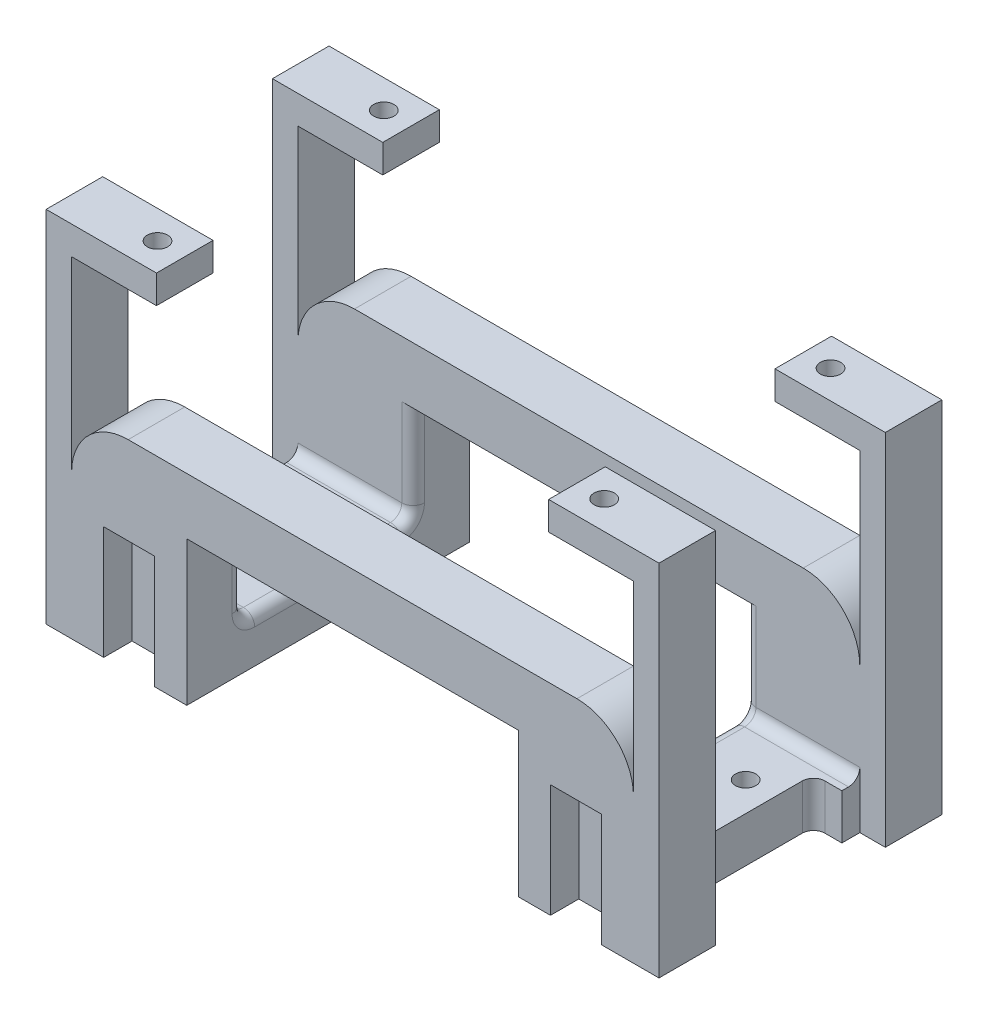
SolidWorks part; units mm, degrees
ref_plane "Front Plane" through (0, 0, 0) normal (0, 0, 1) x (1, 0, 0)
ref_plane "Top Plane" through (0, 0, 0) normal (0, 1, 0) x (1, 0, 0)
ref_plane "Right Plane" through (0, 0, 0) normal (1, 0, 0) x (0, 0, -1)
sketch "Sketch1" plane through (0, 0, 0) normal (0, 0, 1) x (1, 0, 0)
  line L0 (-68.6919, -39.7304) -> (-48.3319, -39.7304)
  line L1 (-48.3319, -39.7304) -> (-48.3319, -14.2304)
  line L2 (-48.3319, -14.2304) -> (10.2681, -14.2304)
  line L3 (10.2681, -14.2304) -> (10.2681, -39.7304)
  line L4 (10.2681, -39.7304) -> (30.6281, -39.7304)
  line L5 (30.6281, -39.7304) -> (30.6281, -4.2304)
  line L6 (30.6281, -4.2304) -> (-68.6919, -4.2304)
  line L7 (-68.6919, -4.2304) -> (-68.6919, -39.7304)
  line L8 (-48.3319, -14.2304) -> (-48.3319, -4.2304) construction
  dimension "D1" = 58.6
  dimension "D2" = 25.5
  dimension "D3" = 99.32
  dimension "D4" = 10
extrude "Boss-Extrude1" add sketch "Sketch1" along normal blind 10
sketch "Sketch2" plane through (0, 0, 10) normal (0, 0, 1) x (1, 0, 0)
  line L0 (-48.3319, -39.7304) -> (-48.3319, -14.2304) construction
  line L1 (-68.6919, -39.7304) -> (-48.3319, -39.7304)
  line L2 (-68.6919, -39.7304) -> (-68.6919, -31.7304)
  line L3 (-68.6919, -31.7304) -> (-48.3319, -31.7304)
  line L4 (-48.3319, -39.7304) -> (-48.3319, -31.7304)
  line L5 (30.6281, -39.7304) -> (30.6281, -4.2304) construction
  line L6 (10.2681, -39.7304) -> (30.6281, -39.7304)
  line L7 (10.2681, -39.7304) -> (10.2681, -31.7304)
  line L8 (10.2681, -31.7304) -> (30.6281, -31.7304)
  line L9 (30.6281, -39.7304) -> (30.6281, -31.7304)
  dimension "D1" = 8
extrude "Boss-Extrude2" add sketch "Sketch2" along normal blind 30
sketch "Sketch3" plane through (0, 0, 40) normal (0, 0, 1) x (1, 0, 0)
  line L0 (-68.6919, -39.7304) -> (-68.6919, -4.2304)
  line L1 (-68.6919, -4.2304) -> (30.6281, -4.2304)
  line L2 (30.6281, -4.2304) -> (30.6281, -39.7304)
  line L3 (30.6281, -39.7304) -> (10.2681, -39.7304)
  line L4 (10.2681, -39.7304) -> (10.2681, -14.2304)
  line L5 (10.2681, -14.2304) -> (-48.3319, -14.2304)
  line L6 (-48.3319, -14.2304) -> (-48.3319, -39.7304)
  line L7 (-48.3319, -39.7304) -> (-68.6919, -39.7304)
  line L8 (-48.3319, -39.7304) -> (-48.3319, -14.2304) construction
  line L10 (30.6281, -39.7304) -> (30.6281, -4.2304) construction
extrude "Boss-Extrude3" add sketch "Sketch3" along normal blind 10
sketch "Sketch4" plane through (0, -31.7304, 0) normal (0, 1, 0) x (1, 0, 0)
  line L0 (-68.6919, -25) -> (30.6281, -25) construction
  line L1 (-68.6919, -40) -> (-68.6919, -10) construction
  line L3 (30.6281, -40) -> (30.6281, -10) construction
  line L4 (-58.5119, -10) -> (-58.5119, -40) construction
  line L5 (-48.3319, -10) -> (-68.6919, -10) construction
  line L6 (-48.3319, -40) -> (-68.6919, -40) construction
  line L7 (20.4481, -10) -> (20.4481, -40) construction
  line L8 (30.6281, -10) -> (10.2681, -10) construction
  line L9 (30.6281, -40) -> (10.2681, -40) construction
  circle A0 centre (-58.5119, -20) radius 1.8
  circle A1 centre (-58.5119, -30) radius 1.8
  circle A2 centre (20.4481, -30) radius 1.8
  circle A3 centre (20.4481, -20) radius 1.8
  dimension "D1" = 3.6
  dimension "D2" = 10
extrude "Cut-Extrude1" cut sketch "Sketch4" against normal through all
sketch "Sketch5" plane through (0, -31.7304, 0) normal (0, 1, 0) x (1, 0, 0)
  line L0 (-68.6919, -40) -> (-68.6919, -10) construction
  line L1 (-68.6919, -13.5) -> (-65.6919, -13.5)
  line L2 (-68.6919, -13.5) -> (-68.6919, -36.5)
  line L3 (-68.6919, -36.5) -> (-65.6919, -36.5)
  line L4 (-63.6919, -15.5) -> (-63.6919, -34.5)
  line L5 (30.6281, -40) -> (30.6281, -10) construction
  line L6 (30.6281, -13.175) -> (27.6281, -13.175)
  line L7 (30.6281, -13.175) -> (30.6281, -36.175)
  line L8 (30.6281, -36.175) -> (27.6281, -36.175)
  line L9 (25.6281, -15.175) -> (25.6281, -34.175)
  line L10 (-68.6919, -25) -> (30.6281, -25) construction
  arc A0 (27.6281, -13.175) -> (25.6281, -15.175) centre (27.6281, -15.175) ccw
  arc A1 (25.6281, -34.175) -> (27.6281, -36.175) centre (27.6281, -34.175) ccw
  arc A2 (-65.6919, -36.5) -> (-63.6919, -34.5) centre (-65.6919, -34.5) ccw
  arc A3 (-63.6919, -15.5) -> (-65.6919, -13.5) centre (-65.6919, -15.5) ccw
  point P20 (-63.6919, -36.5)
  point P23 (-63.6919, -13.5)
  dimension "D3" = 2
  dimension "D1" = 23
  dimension "D2" = 5
extrude "Cut-Extrude2" cut sketch "Sketch5" against normal through all
fillet "Fillet2" radius 10 4 edges at (30.6281, -4.2304, 5) (30.6281, -4.2304, 45) (-68.6919, -4.2304, 5) (-68.6919, -4.2304, 45)
fillet "Fillet3" radius 2 4 edges at (20.4481, -31.7304, 10)
fillet "Fillet4" radius 2 10 edges at (10.2681, -31.1447, 39.4142) (10.2681, -21.9804, 10) (10.2681, -31.1447, 10.5858) (-48.3319, -31.1447, 39.4142) (-48.3319, -31.1447, 10.5858)
sketch "Sketch6" plane through (0, 0, 50) normal (0, 0, 1) x (1, 0, 0)
  line L0 (-68.6919, -39.7304) -> (-48.3319, -39.7304) construction
  line L1 (-63.0119, -39.7304) -> (-54.0119, -39.7304)
  line L2 (-63.0119, -39.7304) -> (-63.0119, -19.7304)
  line L3 (-63.0119, -19.7304) -> (-54.0119, -19.7304)
  line L4 (-54.0119, -39.7304) -> (-54.0119, -19.7304)
  line L5 (10.2681, -39.7304) -> (30.6281, -39.7304) construction
  line L6 (15.9481, -39.7304) -> (24.9481, -39.7304)
  line L7 (15.9481, -39.7304) -> (15.9481, -19.7304)
  line L8 (15.9481, -19.7304) -> (24.9481, -19.7304)
  line L9 (24.9481, -39.7304) -> (24.9481, -19.7304)
  line L10 (-58.5119, -39.7304) -> (-58.5119, 3.4063) construction
  line L11 (20.4481, -39.7304) -> (20.4481, -0.4667) construction
  dimension "D1" = 9
  dimension "D2" = 20
extrude "Cut-Extrude3" cut sketch "Sketch6" against normal blind 5
sketch "Sketch7" plane through (0, 0, 0) normal (0, 0, -1) x (-1, 0, 0)
  line L0 (-20.4481, -39.7304) -> (-20.4481, 23.0749) construction
  line L1 (58.5119, -19.7304) -> (58.5119, -39.7304) construction
  line L2 (-10.2681, -39.7304) -> (-30.6281, -39.7304) construction
  line L3 (68.6919, -39.7304) -> (48.3319, -39.7304) construction
  line L5 (-24.9481, -19.7304) -> (-15.9481, -19.7304)
  line L6 (-24.9481, -19.7304) -> (-24.9481, -39.7304)
  line L7 (-24.9481, -39.7304) -> (-15.9481, -39.7304)
  line L8 (-15.9481, -19.7304) -> (-15.9481, -39.7304)
  line L9 (54.0119, -19.7304) -> (63.0119, -19.7304)
  line L10 (54.0119, -19.7304) -> (54.0119, -39.7304)
  line L11 (54.0119, -39.7304) -> (63.0119, -39.7304)
  line L12 (63.0119, -19.7304) -> (63.0119, -39.7304)
  line L13 (-24.9481, -39.7304) -> (-24.9481, -19.7304) construction
extrude "Cut-Extrude4" cut sketch "Sketch7" against normal blind 5
sketch "Sketch8" plane through (30.6281, 0, 0) normal (1, 0, 0) x (0, 0, -1)
  line L0 (-40, -29.7304) -> (-40, -14.2304) construction
  line L1 (-50, -39.7304) -> (-40, -39.7304)
  line L2 (-50, -39.7304) -> (-50, 23.7696)
  line L3 (-50, 23.7696) -> (-40, 23.7696)
  line L4 (-40, -39.7304) -> (-40, 23.7696)
  line L5 (-10, -39.7304) -> (0, -39.7304)
  line L6 (-10, -39.7304) -> (-10, 23.7696)
  line L7 (-10, 23.7696) -> (0, 23.7696)
  line L8 (0, -39.7304) -> (0, 23.7696)
  line L11 (-10, -29.7304) -> (-10, -14.2304) construction
  line L12 (-40, -14.2304) -> (-50, -14.2304) construction
  dimension "D1" = 38
extrude "Boss-Extrude4" add sketch "Sketch8" along normal blind 4.5
sketch "Sketch9" plane through (30.6281, 0, 0) normal (-1, 0, 0) x (0, 0, 1)
  line L0 (10, 23.7696) -> (10, -14.2304) construction
  line L1 (0, 23.7696) -> (10, 23.7696)
  line L2 (0, 23.7696) -> (0, 18.7696)
  line L3 (0, 18.7696) -> (10, 18.7696)
  line L4 (10, 23.7696) -> (10, 18.7696)
  line L5 (50, 23.7696) -> (50, -14.2304) construction
  line L6 (40, 23.7696) -> (50, 23.7696)
  line L7 (40, 23.7696) -> (40, 18.7696)
  line L8 (40, 18.7696) -> (50, 18.7696)
  line L9 (50, 23.7696) -> (50, 18.7696)
  dimension "D1" = 5
extrude "Boss-Extrude5" add sketch "Sketch9" along normal blind 15
sketch "Sketch10" plane through (-68.6919, 0, 0) normal (-1, 0, 0) x (0, 0, 1)
  line L0 (10, -14.2304) -> (10, -29.7304) construction
  line L1 (0, -39.7304) -> (10, -39.7304)
  line L2 (0, -39.7304) -> (0, 23.7696)
  line L3 (0, 23.7696) -> (10, 23.7696)
  line L4 (10, -39.7304) -> (10, 23.7696)
  line L5 (40, -14.2304) -> (40, -29.7304) construction
  line L6 (50, -39.7304) -> (40, -39.7304)
  line L7 (50, -39.7304) -> (50, 23.7696)
  line L8 (50, 23.7696) -> (40, 23.7696)
  line L9 (40, -39.7304) -> (40, 23.7696)
extrude "Boss-Extrude6" add sketch "Sketch10" along normal blind 4.5
sketch "Sketch11" plane through (-68.6919, 0, 0) normal (1, 0, 0) x (0, 0, -1)
  line L0 (-40, 23.7696) -> (-40, -14.2304) construction
  line L1 (-50, 23.7696) -> (-40, 23.7696)
  line L2 (-50, 23.7696) -> (-50, 18.7696)
  line L3 (-50, 18.7696) -> (-40, 18.7696)
  line L4 (-40, 23.7696) -> (-40, 18.7696)
  line L5 (0, 23.7696) -> (0, -14.2304) construction
  line L6 (-10, 23.7696) -> (0, 23.7696)
  line L7 (-10, 23.7696) -> (-10, 18.7696)
  line L8 (-10, 18.7696) -> (0, 18.7696)
  line L9 (0, 23.7696) -> (0, 18.7696)
  line L10 (-50, -14.2304) -> (-50, 23.7696) construction
  line L11 (-10, -14.2304) -> (-10, 23.7696) construction
extrude "Boss-Extrude7" add sketch "Sketch11" along normal blind 15
sketch "Sketch12" plane through (0, 23.7696, 0) normal (0, 1, 0) x (1, 0, 0)
  line L0 (-73.1919, 0) -> (-53.6919, 0) construction
  line L1 (-19.0319, 24.3919) -> (-19.0319, -50) construction
  line L2 (20.6281, -50) -> (-58.6919, -50) construction
  circle A0 centre (20.4481, -45) radius 1.8
  circle A1 centre (20.4481, -5) radius 1.8
  circle A2 centre (-58.5119, -45) radius 1.8
  circle A3 centre (-58.5119, -5) radius 1.8
  dimension "D2" = 3.6
  dimension "D1" = 40
  dimension "D3" = 5
  dimension "D4" = 78.96
extrude "Cut-Extrude5" cut sketch "Sketch12" against normal up to surface (5 mm away) up to face at (-61.1919, 18.7696, 45)
